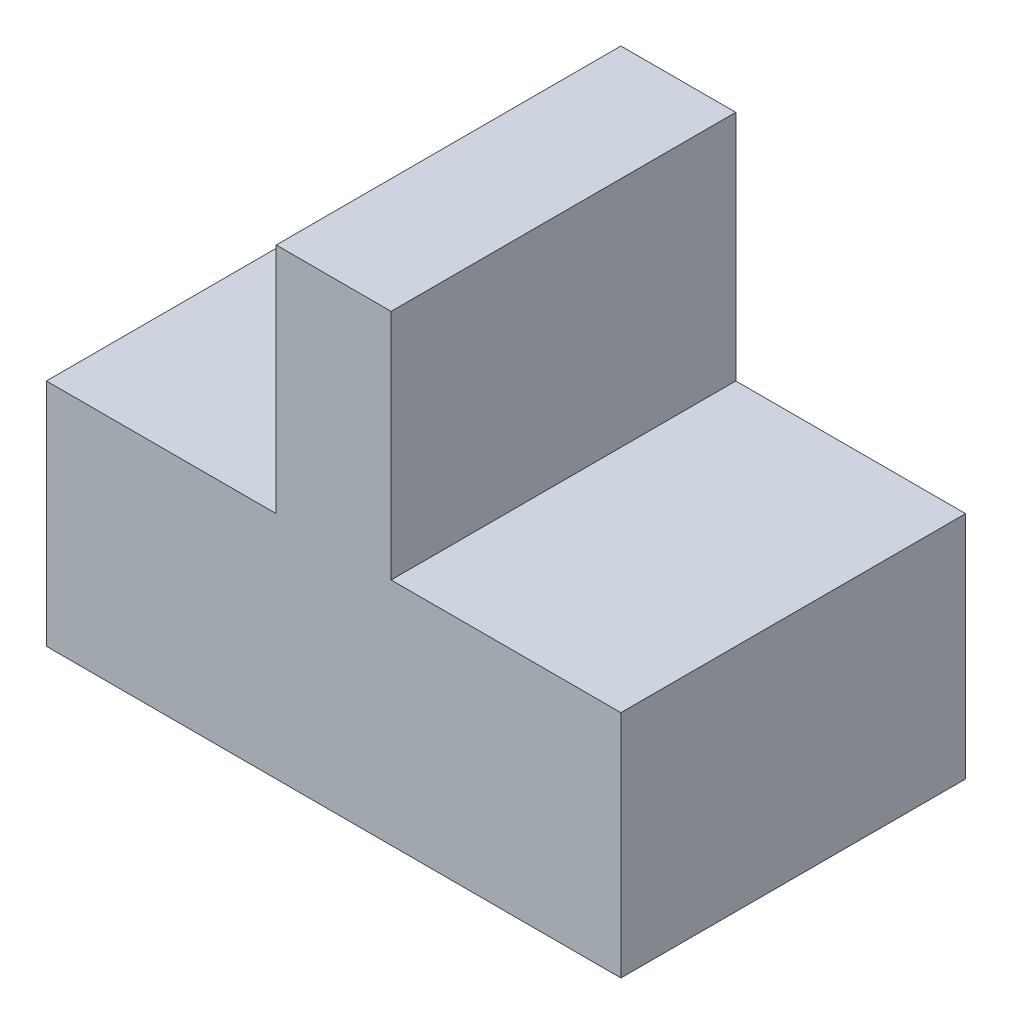
SolidWorks part; units mm, degrees
ref_plane "Plano frontal" through (0, 0, 0) normal (0, 0, 1) x (1, 0, 0)
ref_plane "Plano superior" through (0, 0, 0) normal (0, 1, 0) x (1, 0, 0)
ref_plane "Plano direito" through (0, 0, 0) normal (1, 0, 0) x (0, 0, -1)
sketch "Esboço3" plane through (0, 0, 0) normal (0, 0, 1) x (1, 0, 0)
  line L0 (0, 0) -> (50, 0)
  line L1 (50, 0) -> (50, 20)
  line L2 (50, 20) -> (30, 20)
  line L3 (30, 20) -> (30, 40.2477)
  line L4 (30, 40.2477) -> (20, 40.2477)
  line L5 (20, 40.2477) -> (20, 20)
  line L6 (20, 20) -> (0, 20)
  line L7 (0, 20) -> (0, 0)
  dimension "D2" = 20
  dimension "D3" = 50
  dimension "D5" = 20
  dimension "D6" = 10
extrude "Ressalto-extrusão3" add sketch "Esboço3" along normal blind 30
